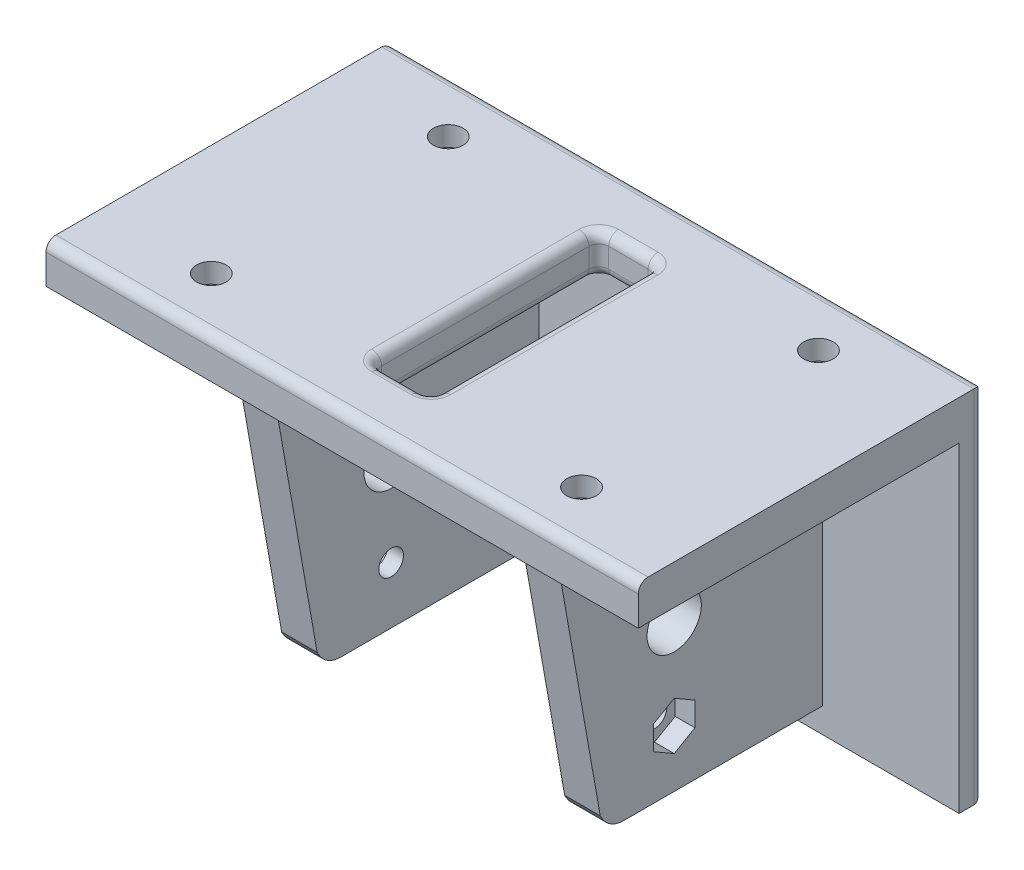
SolidWorks part; units mm, degrees
ref_plane "Front Plane" through (0, 0, 0) normal (0, 0, 1) x (1, 0, 0)
ref_plane "Top Plane" through (0, 0, 0) normal (0, 1, 0) x (1, 0, 0)
ref_plane "Right Plane" through (0, 0, 0) normal (1, 0, 0) x (0, 0, -1)
sketch "Sketch1" plane through (0, 0, 0) normal (0, 1, 0) x (1, 0, 0)
  line L0 (0, 18.2197) -> (0, -18.3609) construction
  line L1 (-19.3496, 0) -> (20.197, 0) construction
  line L2 (-37.5, 0) -> (-37.5, -10) construction
  line L3 (60, 35) -> (-60, 35)
  line L4 (-60, 35) -> (-60, -35)
  line L5 (60, -35) -> (-60, -35)
  line L6 (60, 35) -> (60, -35)
  line L7 (6, 23) -> (-6, 23)
  line L8 (-6, 23) -> (-6, -23)
  line L9 (6, -23) -> (-6, -23)
  line L10 (6, 23) -> (6, -23)
  circle A0 centre (-37.5, 0) radius 10 construction
  circle A6 centre (-37.5, 24) radius 3
  circle A7 centre (-37.5, 24) radius 3.4 construction
  circle A8 centre (-37.5, -24) radius 3
  circle A9 centre (-37.5, -24) radius 3.4 construction
  circle A10 centre (37.5, 24) radius 3
  circle A11 centre (37.5, 24) radius 3.4 construction
  circle A12 centre (37.5, 0) radius 10 construction
  circle A13 centre (37.5, -24) radius 3.4 construction
  circle A14 centre (37.5, -24) radius 3
  point P18 (-60, 0)
  point P20 (0, 35)
  point P21 (0, -35)
  point P33 (-6, 0)
  point P35 (0, -23)
  point P36 (0, 23)
  dimension "D1" = 20
  dimension "D3" = 6.8
  dimension "D4" = 48
  dimension "D5" = 75
  dimension "D2" = 6
  dimension "D6" = 120
  dimension "D7" = 70
  dimension "D8" = 12
  dimension "D9" = 46
extrude "Boss-Extrude1" add sketch "Sketch1" along normal blind 8
fillet "Fillet1" radius 2 4 edges at (6, 4, 23) (-6, 4, 23) (6, 4, -23) (-6, 4, -23)
sketch "Sketch2" plane through (0, 0, 0) normal (0, -1, 0) x (1, 0, 0)
  line L0 (-60, -35) -> (-60, -30)
  line L1 (-60, -35) -> (-60, 35) construction
  line L2 (-60, -30) -> (60, -30)
  line L3 (60, 35) -> (60, -35) construction
  line L4 (60, -30) -> (60, -35)
  line L5 (60, -35) -> (-60, -35)
  dimension "D1" = 5
extrude "Boss-Extrude2" add sketch "Sketch2" along normal blind 65
sketch "Sketch3" plane through (0, 0, -30) normal (0, 0, 1) x (1, 0, 0)
  line L0 (0, 0) -> (0, -65) construction
  line L1 (60, 0) -> (-60, 0) construction
  line L2 (60, -65) -> (-60, -65) construction
  line L3 (0, -32.5) -> (-60, -32.5) construction
  line L4 (-60, -65) -> (-60, 0) construction
  line L5 (0, -32.5) -> (60, -32.5) construction
  line L6 (60, -65) -> (60, 0) construction
  line L8 (30, 0) -> (30, -65) construction
  line L9 (-25.075, 0) -> (-32.275, 0)
  line L10 (-32.275, 0) -> (-32.275, -60)
  line L11 (-32.275, -60) -> (-25.075, -60)
  line L12 (-25.075, 0) -> (-25.075, -60)
  line L13 (25.075, 0) -> (25.075, -60)
  line L14 (32.275, -60) -> (25.075, -60)
  line L15 (32.275, 0) -> (32.275, -60)
  line L16 (25.075, 0) -> (32.275, 0)
  point P18 (30, -32.5)
  dimension "D1" = 7.2
  dimension "D2" = 50.15
  dimension "D3" = 60
extrude "Boss-Extrude3" add sketch "Sketch3" along normal blind 45
sketch "Sketch4" plane through (-32.275, 0, 0) normal (-1, 0, 0) x (0, 0, 1)
  line L0 (0, 0) -> (0, -60) construction
  line L1 (15, -60) -> (-30, -60) construction
  line L2 (-30, -30) -> (15, -30) construction
  line L3 (-30, 0) -> (-30, -60) construction
  line L4 (15, 0) -> (15, -60) construction
  circle A0 centre (0, -30) radius 5.5
  circle A1 centre (0, -30) radius 18.5 construction
  circle A2 centre (0, -11.5) radius 2.5
  circle A3 centre (0, -48.5) radius 2.5
  dimension "D1" = 11
  dimension "D2" = 37
  dimension "5" = 5
extrude "Cut-Extrude1" cut sketch "Sketch4" against normal through all both and the other way through all
sketch "Sketch5" plane through (-32.275, 0, 0) normal (-1, 0, 0) x (0, 0, 1)
  line L0 (-30, 0) -> (-30, -60) construction
  line L1 (4.2, -9.0751) -> (0, -6.6503)
  line L2 (0, -6.6503) -> (-4.2, -9.0751)
  line L3 (-4.2, -9.0751) -> (-4.2, -13.9249)
  line L4 (-4.2, -13.9249) -> (0, -16.3497)
  line L5 (0, -16.3497) -> (4.2, -13.9249)
  line L6 (4.2, -13.9249) -> (4.2, -9.0751)
  line L7 (4.2, -46.0751) -> (0, -43.6503)
  line L8 (0, -43.6503) -> (-4.2, -46.0751)
  line L9 (-4.2, -46.0751) -> (-4.2, -50.9249)
  line L10 (-4.2, -50.9249) -> (0, -53.3497)
  line L11 (0, -53.3497) -> (4.2, -50.9249)
  line L12 (4.2, -50.9249) -> (4.2, -46.0751)
  line L13 (-30, -65) -> (-30, 0) construction
  circle A0 centre (0, -11.5) radius 4.2 construction
  circle A1 centre (0, -48.5) radius 4.2 construction
  point P10 (2.1, -52.1373)
  dimension "D1" = 8.4
  dimension "D2" = 8.4
extrude "Cut-Extrude2" cut sketch "Sketch5" against normal blind 4
sketch "Sketch6" plane through (32.275, 0, 0) normal (1, 0, 0) x (0, 0, -1)
  line L0 (30, -65) -> (30, 0) construction
  line L1 (4.2, -13.9249) -> (4.2, -9.0751)
  line L2 (4.2, -9.0751) -> (0, -6.6503)
  line L3 (0, -6.6503) -> (-4.2, -9.0751)
  line L4 (-4.2, -9.0751) -> (-4.2, -13.9249)
  line L5 (-4.2, -13.9249) -> (0, -16.3497)
  line L6 (0, -16.3497) -> (4.2, -13.9249)
  line L7 (-4.2, -46.0751) -> (-4.2, -50.9249)
  line L8 (-4.2, -50.9249) -> (0, -53.3497)
  line L9 (0, -53.3497) -> (4.2, -50.9249)
  line L10 (4.2, -50.9249) -> (4.2, -46.0751)
  line L11 (4.2, -46.0751) -> (0, -43.6503)
  line L12 (0, -43.6503) -> (-4.2, -46.0751)
  circle A0 centre (0, -11.5) radius 4.2 construction
  circle A1 centre (0, -48.5) radius 4.2 construction
  dimension "D1" = 8.4
  dimension "D2" = 8.4
extrude "Cut-Extrude3" cut sketch "Sketch6" against normal blind 4
sketch "Sketch7" plane through (0, 0, 0) normal (0, -1, 0) x (1, 0, 0)
  line L0 (32.275, 15) -> (32.275, -30) construction
  line L1 (42.7, -20.9978) -> (37.5, -17.9956)
  line L2 (37.5, -17.9956) -> (32.3, -20.9978)
  line L3 (32.3, -20.9978) -> (32.3, -27.0022)
  line L4 (32.3, -27.0022) -> (37.5, -30.0044)
  line L5 (37.5, -30.0044) -> (42.7, -27.0022)
  line L6 (42.7, -27.0022) -> (42.7, -20.9978)
  line L7 (42.7, 27.0022) -> (37.5, 30.0044)
  line L8 (37.5, 30.0044) -> (32.3, 27.0022)
  line L9 (32.3, 27.0022) -> (32.3, 20.9978)
  line L10 (32.3, 20.9978) -> (37.5, 17.9956)
  line L11 (37.5, 17.9956) -> (42.7, 20.9978)
  line L12 (42.7, 20.9978) -> (42.7, 27.0022)
  line L13 (0, 0) -> (0, 40) construction
  line L14 (-42.7, -27.0022) -> (-42.7, -20.9978)
  line L15 (-37.5, -30.0044) -> (-42.7, -27.0022)
  line L16 (-32.3, -27.0022) -> (-37.5, -30.0044)
  line L17 (-32.3, -20.9978) -> (-32.3, -27.0022)
  line L18 (-37.5, -17.9956) -> (-32.3, -20.9978)
  line L19 (-42.7, -20.9978) -> (-37.5, -17.9956)
  line L20 (-42.7, 20.9978) -> (-42.7, 27.0022)
  line L21 (-37.5, 17.9956) -> (-42.7, 20.9978)
  line L22 (-32.3, 20.9978) -> (-37.5, 17.9956)
  line L23 (-32.3, 27.0022) -> (-32.3, 20.9978)
  line L24 (-37.5, 30.0044) -> (-32.3, 27.0022)
  line L25 (-42.7, 27.0022) -> (-37.5, 30.0044)
  circle A0 centre (37.5, -24) radius 5.2 construction
  circle A1 centre (37.5, 24) radius 5.2 construction
  circle A3 centre (-37.5, -24) radius 5.2 construction
  circle A4 centre (-37.5, 24) radius 5.2 construction
  dimension "D1" = 10.4
  dimension "D2" = 10.4
extrude "Cut-Extrude4" cut sketch "Sketch7" against normal blind 4
sketch "Sketch8" plane through (32.275, 0, 0) normal (1, 0, 0) x (0, 0, -1)
  circle A0 centre (0, -30) radius 9.515 construction
  circle A1 centre (0, -20.485) radius 1.5
  circle A2 centre (0, -39.515) radius 1.5
  dimension "D1" = 19.03
  dimension "D2" = 3
extrude "Cut-Extrude5" [suppressed] cut sketch "Sketch8" against normal up to surface (7.2 mm away)
sketch "Sketch9" [suppressed] plane through (25.075, 0, 0) normal (-1, 0, 0) x (0, 0, 1)
  line L1 (1.7321, -40.015) -> (3.4641, -37.015)
  line L2 (3.4641, -37.015) -> (1.7321, -34.015)
  line L3 (1.7321, -34.015) -> (-1.7321, -34.015)
  line L4 (-1.7321, -34.015) -> (-3.4641, -37.015)
  line L5 (-3.4641, -37.015) -> (-1.7321, -40.015)
  line L6 (-1.7321, -40.015) -> (1.7321, -40.015)
  line L7 (1.7321, -20.985) -> (3.4641, -17.985)
  line L8 (3.4641, -17.985) -> (1.7321, -14.985)
  line L9 (1.7321, -14.985) -> (-1.7321, -14.985)
  line L10 (-1.7321, -14.985) -> (-3.4641, -17.985)
  line L11 (-3.4641, -17.985) -> (-1.7321, -20.985)
  line L12 (-1.7321, -20.985) -> (1.7321, -20.985)
  line L13 (15, -55) -> (-30, -55) construction
  circle A0 centre (0, -37.015) radius 3 construction
  circle A1 centre (0, -17.985) radius 3 construction
  dimension "D1" = 6
  dimension "D2" = 6
extrude "Cut-Extrude6" [suppressed] cut sketch "Sketch9" against normal blind 3.5
chamfer "Chamfer1" distance 10 angle 80 2 edges at (-28.675, 0, 15) (28.675, 0, 15)
fillet "Fillet3" radius 2 21 edges at (5.4142, 0, 22.4142) (0, 0, 23) (-5.4142, 0, 22.4142) (-6, 0, 0) (-5.4142, 0, -22.4142) (0, 0, -23) (5.4142, 0, -22.4142) (5.4142, 8, 22.4142) (0, 8, 23) (-5.4142, 8, 22.4142) (-6, 8, 0) (-5.4142, 8, -22.4142) (0, 8, -23) (5.4142, 8, -22.4142) (0, 8, -35) (-60, -28.5, -35) (0, -65, -35) (60, -28.5, -35) (6, 0, 0) (6, 8, 0) (0, 8, 35)
chamfer "Chamfer2" distance 2 angle 58 2 edges at (28.675, -60, 15) (-28.675, -60, 15)
fillet "Fillet4" radius 5 2 edges at (-28.675, -60, 13) (28.675, -60, 13)
